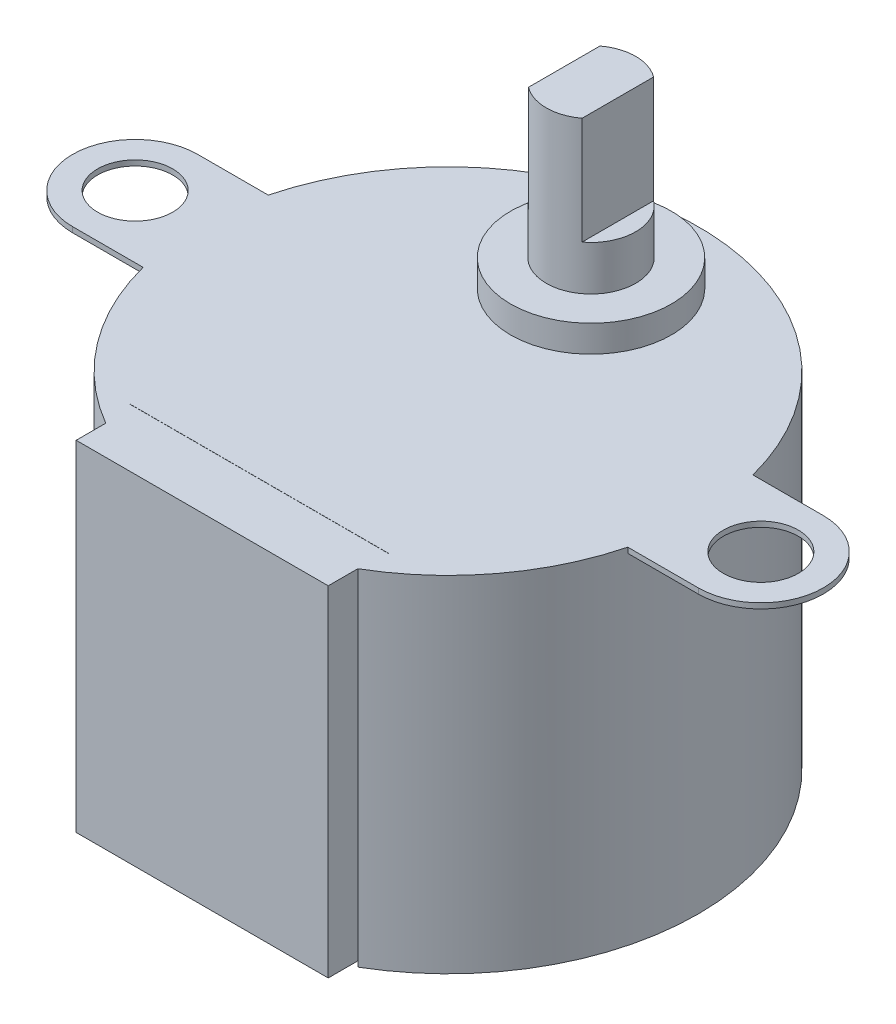
SolidWorks part; units mm, degrees
material "1060-H12 Vareta (SS)"
ref_plane "Plano frontal" through (0, 0, 0) normal (0, 0, 1) x (1, 0, 0)
ref_plane "Plano superior" through (0, 0, 0) normal (0, 1, 0) x (1, 0, 0)
ref_plane "Plano direito" through (0, 0, 0) normal (1, 0, 0) x (0, 0, -1)
sketch "Esboço18" plane through (0, 0, 0) normal (0, 1, 0) x (1, 0, 0)
  line L2 (-7.3, -11.3561) -> (-7.3, -10.5)
  line L3 (-7.3, -10.5) -> (7.3, -10.5)
  line L4 (7.3, -11.3561) -> (7.3, -10.5)
  line L6 (-7.05, -12.0954) -> (-7.05, -10.75)
  line L7 (-7.05, -10.75) -> (7.05, -10.75)
  line L8 (7.05, -12.0954) -> (7.05, -10.75)
  arc A0 (7.05, -12.0954) -> (-7.05, -12.0954) centre (0, 0) ccw
  arc A1 (7.3, -11.3561) -> (-7.3, -11.3561) centre (0, 0) ccw
extrude "Ressalto-extrusão11" add sketch "Esboço18" along normal blind 19 contours A0 L6 L7 L8 | A1 L2 L3 L4
sketch "Esboço20" plane through (0, 19, 0) normal (0, 1, 0) x (1, 0, 0)
  line L0 (17.3735, 0) -> (-17.6265, 0) construction
  line L1 (17.3735, -3.5) -> (-17.6265, -3.5)
  line L2 (17.3735, 3.5) -> (-17.6265, 3.5)
  arc A0 (17.3735, -3.5) -> (17.3735, 3.5) centre (17.3735, 0) ccw
  arc A1 (-17.6265, 3.5) -> (-17.6265, -3.5) centre (-17.6265, 0) ccw
  point P3 (-0.1265, 0)
extrude "Corte-extrusão4" cut sketch "Esboço20" against normal blind 0.3
sketch "Esboço21" plane through (0, 18.7, 0) normal (0, 1, 0) x (1, 0, 0)
  line L0 (-33.9964, 0) -> (32.3508, 0) construction
  line L1 (17.5, -3.5) -> (13.0384, -3.5)
  line L2 (17.5, 3.5) -> (13.0384, 3.5)
  line L5 (-7.2872, -11.3643) -> (-7.2872, -10.491)
  line L6 (-7.2872, -10.491) -> (7.2794, -10.491)
  line L7 (7.2794, -11.3693) -> (7.2794, -10.491)
  line L8 (-13.0384, -3.5) -> (-17.5, -3.5)
  line L9 (-13.0384, 3.5) -> (-17.5, 3.5)
  arc A0 (17.5, -3.5) -> (17.5, 3.5) centre (17.5, 0) ccw
  arc A1 (-17.5, 3.5) -> (-17.5, -3.5) centre (-17.5, 0) ccw
  circle A2 centre (-17.5, 0) radius 2.1
  circle A3 centre (17.5, 0) radius 2.1
  arc A4 (7.2794, -11.3693) -> (13.0384, -3.5) centre (0, 0) ccw
  arc A5 (-13.0384, -3.5) -> (-7.2872, -11.3643) centre (0, 0) ccw
  arc A6 (13.0384, 3.5) -> (-13.0384, 3.5) centre (0, 0) ccw
  circle A7 centre (0, 8) radius 4.5
  dimension "D1" = 9
  dimension "D2" = 4.2
  dimension "D3" = 4.2
  dimension "D4" = 8
extrude "Ressalto-extrusão17" add sketch "Esboço21" along normal blind 0.3
sketch "Esboço22" plane through (0, 0, 0) normal (0, -1, 0) x (1, 0, 0)
  line L1 (-7.0493, 10.7439) -> (7.0627, 10.7439)
  line L2 (-7.0493, 10.7439) -> (-7.0493, 12.0957)
  line L4 (7.0627, 10.7439) -> (7.0627, 12.088)
  arc A0 (-7.0493, 12.0957) -> (7.0627, 12.088) centre (0, 0) ccw
extrude "Ressalto-extrusão18" add sketch "Esboço22" along normal blind 0.3
sketch "Esboço25" plane through (0, 19, 0) normal (0, 1, 0) x (1, 0, 0)
  circle A0 centre (0, 8) radius 4.5
  dimension "D1" = 9
extrude "Ressalto-extrusão21" add sketch "Esboço25" along normal blind 1.5 separate body
sketch "Esboço27" plane through (0, 20.5, 0) normal (0, 1, 0) x (1, 0, 0)
  circle A0 centre (0, 8) radius 2.5
extrude "Ressalto-extrusão22" add sketch "Esboço27" along normal blind 8.5
sketch "Esboço28" plane through (0, 29, 0) normal (0, 1, 0) x (1, 0, 0)
  line L1 (1.5, 10) -> (1.5, 6)
  line L2 (-1.5, 10) -> (-1.5, 6)
  arc A2 (-1.5, 10) -> (-1.5, 6) centre (0, 8) ccw
  circle A3 centre (0, 8) radius 2.5 construction
  arc A4 (1.5, 10) -> (1.5, 6) centre (0, 8) cw
extrude "Corte-extrusão5" cut sketch "Esboço28" against normal blind 6
sketch "Esboço29" plane through (0, 0, 0) normal (0, 1, 0) x (1, 0, 0)
  line L1 (-7.05, -13.75) -> (7.05, -13.75)
  line L2 (-7.05, -13.75) -> (-7.05, -10.75)
  line L3 (-7.05, -10.75) -> (7.05, -10.75)
  line L4 (7.05, -13.75) -> (7.05, -10.75)
extrude "Ressalto-extrusão24" add sketch "Esboço29" along normal blind 19 contours L1 L4 L3 L2
